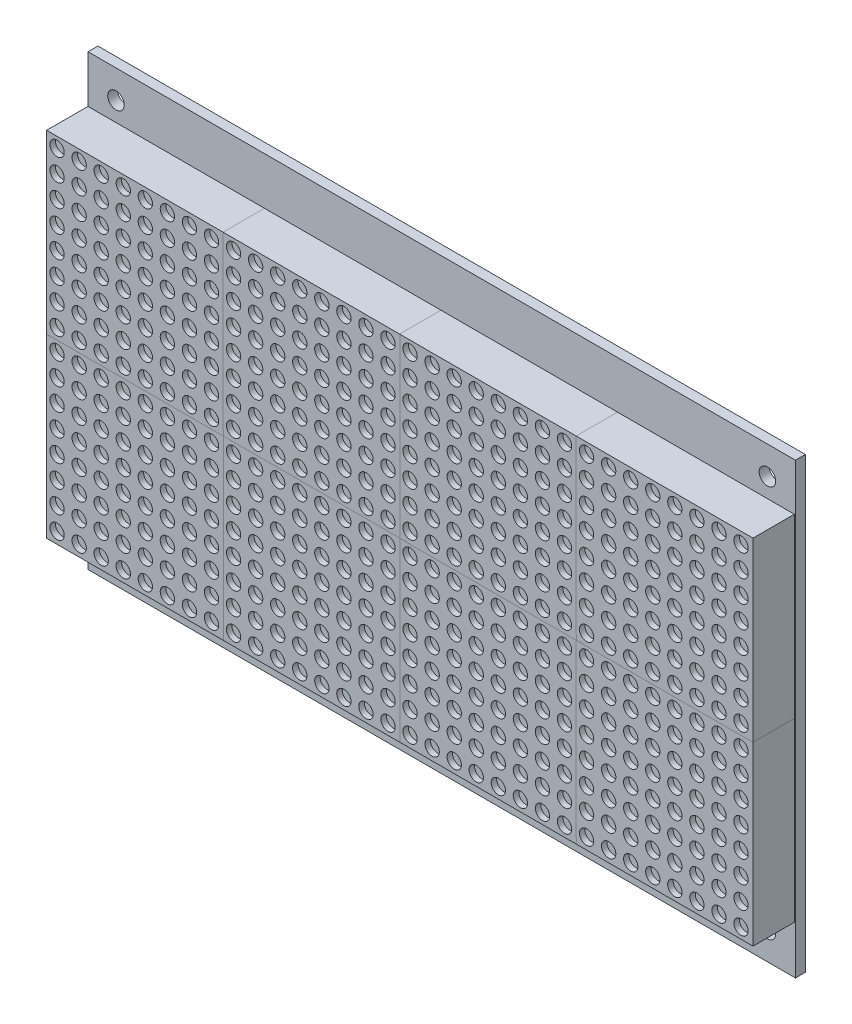
SolidWorks part; units mm, degrees
ref_plane "Front Plane" through (0, 0, 0) normal (0, 0, 1) x (1, 0, 0)
ref_plane "Top Plane" through (0, 0, 0) normal (0, 1, 0) x (1, 0, 0)
ref_plane "Right Plane" through (0, 0, 0) normal (1, 0, 0) x (0, 0, -1)
sketch "Sketch1" plane through (0, 0, 0) normal (0, 0, 1) x (1, 0, 0)
  line L0 (5.08, 76.2) -> (5.08, 81.3) construction
  line L1 (0, 0) -> (128.27, 0)
  line L2 (0, 0) -> (0, 81.3)
  line L3 (0, 81.3) -> (128.27, 81.3)
  line L4 (128.27, 0) -> (128.27, 81.3)
  line L5 (5.08, 76.2) -> (0, 76.2) construction
  line L6 (64.135, 81.3) -> (64.135, 0) construction
  line L7 (0, 40.65) -> (128.27, 40.65) construction
  circle A0 centre (5.08, 76.2) radius 1.5
  circle A1 centre (123.19, 76.2) radius 1.5
  circle A2 centre (123.19, 5.1) radius 1.5
  circle A3 centre (5.08, 5.1) radius 1.5
  dimension "D3" = 5.08
  dimension "D5" = 3
  dimension "D1" = 128.27
  dimension "D2" = 81.3
  dimension "D4" = 5.1
extrude "Boss-Extrude1" add sketch "Sketch1" along normal blind 1.8
sketch "Sketch2" plane through (0, 0, 1.8) normal (0, 0, 1) x (1, 0, 0)
  line L0 (0, 40.65) -> (128.27, 40.65) construction
  line L1 (0, 81.3) -> (0, 0) construction
  line L2 (128.27, 0) -> (128.27, 81.3) construction
  line L3 (64.135, 81.3) -> (64.135, 0) construction
  line L4 (128.27, 81.3) -> (0, 81.3) construction
  line L5 (0, 0) -> (128.27, 0) construction
  line L6 (64.135, 81.3) -> (0, 81.3) construction
  line L7 (32.0675, 81.3) -> (32.0675, 40.65) construction
  line L9 (0, 40.65) -> (32.0675, 40.65)
  line L10 (0, 40.65) -> (0, 72.7175)
  line L11 (0, 72.7175) -> (32.0675, 72.7175)
  line L12 (32.0675, 40.65) -> (32.0675, 72.7175)
extrude "Boss-Extrude2" add sketch "Sketch2" along normal blind 7.5 separate body
sketch "Sketch3" plane through (0, 0, 9.3) normal (0, 0, 1) x (1, 0, 0)
  line L0 (32.0675, 72.7175) -> (0, 72.7175) construction
  line L1 (0, 72.7175) -> (0, 40.65) construction
  circle A0 centre (1.9, 70.8175) radius 1.3
  circle A1 centre (5.9, 70.8) radius 1.3
  circle A2 centre (9.9, 70.7825) radius 1.3
  circle A3 centre (13.9, 70.765) radius 1.3
  circle A4 centre (17.9, 70.7475) radius 1.3
  circle A5 centre (21.9, 70.73) radius 1.3
  circle A6 centre (25.9, 70.7125) radius 1.3
  circle A7 centre (29.9, 70.695) radius 1.3
  circle A8 centre (1.9, 66.8) radius 1.3
  circle A9 centre (5.9, 66.7825) radius 1.3
  circle A10 centre (9.9, 66.765) radius 1.3
  circle A11 centre (13.9, 66.7475) radius 1.3
  circle A12 centre (17.9, 66.73) radius 1.3
  circle A13 centre (21.9, 66.7125) radius 1.3
  circle A14 centre (25.9, 66.695) radius 1.3
  circle A15 centre (29.9, 66.6775) radius 1.3
  circle A16 centre (1.9, 62.7825) radius 1.3
  circle A17 centre (5.9, 62.765) radius 1.3
  circle A18 centre (9.9, 62.7475) radius 1.3
  circle A19 centre (13.9, 62.73) radius 1.3
  circle A20 centre (17.9, 62.7125) radius 1.3
  circle A21 centre (21.9, 62.695) radius 1.3
  circle A22 centre (25.9, 62.6775) radius 1.3
  circle A23 centre (29.9, 62.66) radius 1.3
  circle A24 centre (1.9, 58.765) radius 1.3
  circle A25 centre (5.9, 58.7475) radius 1.3
  circle A26 centre (9.9, 58.73) radius 1.3
  circle A27 centre (13.9, 58.7125) radius 1.3
  circle A28 centre (17.9, 58.695) radius 1.3
  circle A29 centre (21.9, 58.6775) radius 1.3
  circle A30 centre (25.9, 58.66) radius 1.3
  circle A31 centre (29.9, 58.6425) radius 1.3
  circle A32 centre (1.9, 54.7475) radius 1.3
  circle A33 centre (5.9, 54.73) radius 1.3
  circle A34 centre (9.9, 54.7125) radius 1.3
  circle A35 centre (13.9, 54.695) radius 1.3
  circle A36 centre (17.9, 54.6775) radius 1.3
  circle A37 centre (21.9, 54.66) radius 1.3
  circle A38 centre (25.9, 54.6425) radius 1.3
  circle A39 centre (29.9, 54.625) radius 1.3
  circle A40 centre (1.9, 50.73) radius 1.3
  circle A41 centre (5.9, 50.7125) radius 1.3
  circle A42 centre (9.9, 50.695) radius 1.3
  circle A43 centre (13.9, 50.6775) radius 1.3
  circle A44 centre (17.9, 50.66) radius 1.3
  circle A45 centre (21.9, 50.6425) radius 1.3
  circle A46 centre (25.9, 50.625) radius 1.3
  circle A47 centre (29.9, 50.6075) radius 1.3
  circle A48 centre (1.9, 46.7125) radius 1.3
  circle A49 centre (5.9, 46.695) radius 1.3
  circle A50 centre (9.9, 46.6775) radius 1.3
  circle A51 centre (13.9, 46.66) radius 1.3
  circle A52 centre (17.9, 46.6425) radius 1.3
  circle A53 centre (21.9, 46.625) radius 1.3
  circle A54 centre (25.9, 46.6075) radius 1.3
  circle A55 centre (29.9, 46.59) radius 1.3
  circle A56 centre (1.9, 42.695) radius 1.3
  circle A57 centre (5.9, 42.6775) radius 1.3
  circle A58 centre (9.9, 42.66) radius 1.3
  circle A59 centre (13.9, 42.6425) radius 1.3
  circle A60 centre (17.9, 42.625) radius 1.3
  circle A61 centre (21.9, 42.6075) radius 1.3
  circle A62 centre (25.9, 42.59) radius 1.3
  circle A63 centre (29.9, 42.5725) radius 1.3
  dimension "D1" = 2.6
  dimension "D2" = 1.9
  dimension "D3" = 1.9
  dimension "D4" = 8
  dimension "D5" = 8
extrude "Cut-Extrude1" cut sketch "Sketch3" against normal blind 1
pattern_linear "LPattern2" count 4 spacing 32 along (1, 0, 0) count 2 spacing 32 along (0, -1, 0) of bodies 103
sketch "Sketch4" plane through (0, 0, 0) normal (0, 0, -1) x (-1, 0, 0)
  line L1 (-12, 22.4) -> (-42, 22.4)
  line L2 (-12, 22.4) -> (-12, 31)
  line L3 (-12, 31) -> (-42, 31)
  line L4 (-42, 22.4) -> (-42, 31)
  line L6 (0, 81.3) -> (0, 0) construction
  line L7 (0, 0) -> (-128.27, 0) construction
  dimension "D1" = 42
  dimension "D2" = 31
  dimension "D3" = 8.6
  dimension "D4" = 30
extrude "Boss-Extrude3" add sketch "Sketch4" along normal blind 17
